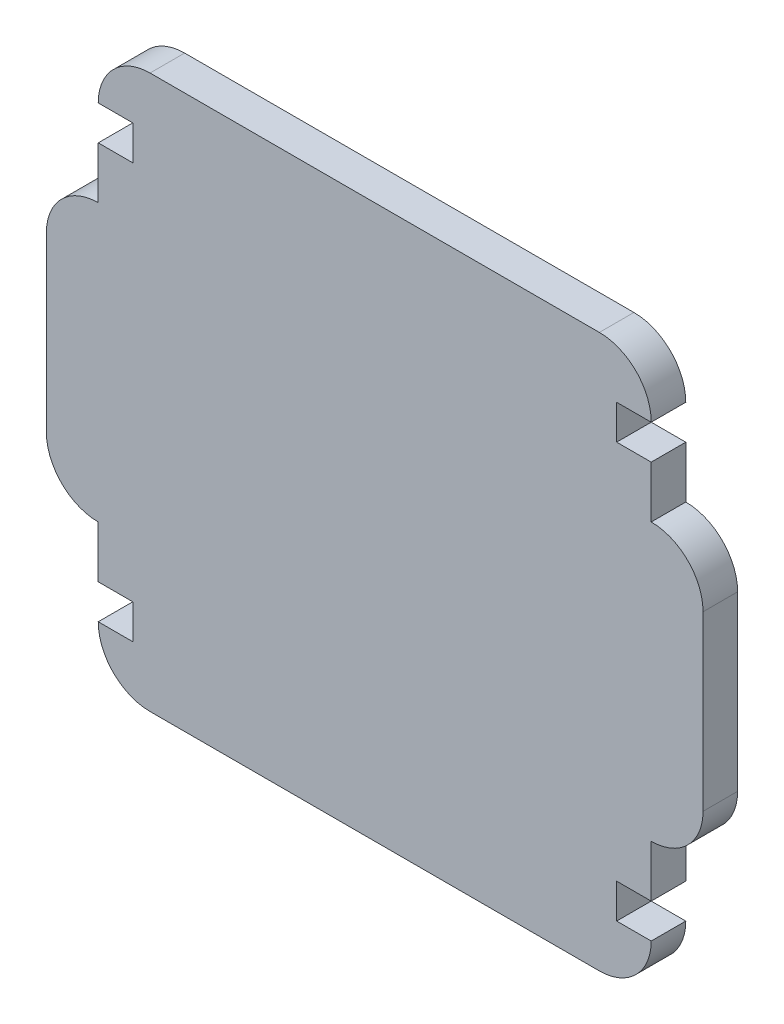
SolidWorks part; units mm, degrees
ref_plane "Front Plane" through (0, 0, 0) normal (0, 0, 1) x (1, 0, 0)
ref_plane "Top Plane" through (0, 0, 0) normal (0, 1, 0) x (1, 0, 0)
ref_plane "Right Plane" through (0, 0, 0) normal (1, 0, 0) x (0, 0, -1)
sketch "Sketch1" plane through (0, 0, 0) normal (0, 0, 1) x (1, 0, 0)
  line L0 (25.4, 17.4625) -> (25.4, 12.7)
  line L1 (-20.6375, 25.4) -> (20.6375, 25.4)
  line L2 (-25.4, 17.4625) -> (-25.4, 12.7)
  line L3 (-20.6375, -25.4) -> (20.6375, -25.4)
  line L6 (22.225, 20.6375) -> (22.225, 17.4625)
  line L7 (-22.225, 20.6375) -> (-25.4, 20.6375)
  line L8 (-25.4, 20.6375) -> (-22.225, 20.6375)
  line L9 (-22.225, 20.6375) -> (-22.225, 17.4625)
  line L10 (-22.225, 17.4625) -> (-25.4, 17.4625)
  line L11 (-25.4, 20.6375) -> (-22.225, 20.6375)
  line L12 (22.225, 17.4625) -> (25.4, 17.4625)
  line L13 (22.225, 20.6375) -> (25.4, 20.6375)
  line L15 (22.225, -17.4625) -> (25.4, -17.4625)
  line L16 (22.225, -20.6375) -> (22.225, -17.4625)
  line L17 (22.225, -20.6375) -> (25.4, -20.6375)
  line L18 (-22.225, -20.6375) -> (-25.4, -20.6375)
  line L19 (-22.225, -20.6375) -> (-22.225, -17.4625)
  line L20 (-22.225, -17.4625) -> (-25.4, -17.4625)
  line L21 (25.4, 17.4625) -> (25.4, 12.7)
  line L23 (30.1625, 7.9375) -> (30.1625, -7.9375)
  line L24 (-30.1625, -7.9375) -> (-30.1625, 7.9375)
  line L25 (-25.4, -12.7) -> (-25.4, -17.4625)
  line L26 (25.4, -12.7) -> (25.4, -17.4625)
  arc A0 (-25.4, 20.6375) -> (-20.6375, 25.4) centre (-20.6375, 20.6375) cw
  arc A1 (25.4, 20.6375) -> (20.6375, 25.4) centre (20.6375, 20.6375) ccw
  arc A2 (25.4, -20.6375) -> (20.6375, -25.4) centre (20.6375, -20.6375) cw
  arc A3 (-25.4, -20.6375) -> (-20.6375, -25.4) centre (-20.6375, -20.6375) ccw
  arc A4 (25.4, 12.7) -> (30.1625, 7.9375) centre (25.4, 7.9375) cw
  arc A5 (25.4, -12.7) -> (30.1625, -7.9375) centre (25.4, -7.9375) ccw
  arc A6 (-25.4, 12.7) -> (-30.1625, 7.9375) centre (-25.4, 7.9375) ccw
  arc A7 (-25.4, -12.7) -> (-30.1625, -7.9375) centre (-25.4, -7.9375) cw
  point P0 (0, 0)
extrude "Boss-Extrude2" add sketch "Sketch1" along normal blind 3.175 contours A7 L25 L20 L19 L18 A3 L3 A2 L17 L16 L15 L26 A5 L23 A4 L0 L12 L6 L13 A1 L1 A0 L7 L9 L10 L2 A6 L24
